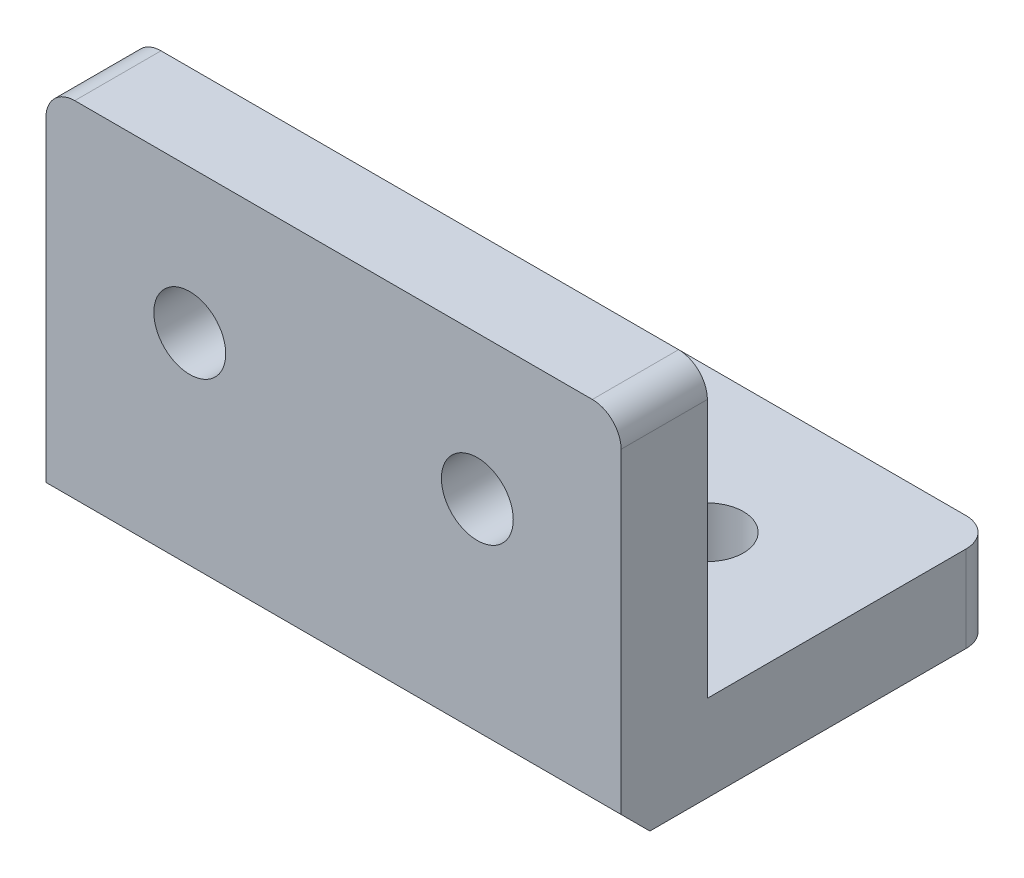
SolidWorks part; units mm, degrees
material "6061 Alloy"
ref_plane "Front Plane" through (0, 0, 0) normal (0, 0, 1) x (1, 0, 0)
ref_plane "Top Plane" through (0, 0, 0) normal (0, 1, 0) x (1, 0, 0)
ref_plane "Right Plane" through (0, 0, 0) normal (1, 0, 0) x (0, 0, -1)
sketch "Sketch1" plane through (0, 0, 0) normal (0, 0, 1) x (1, 0, 0)
  line L0 (-10, 0.75) -> (49990, 0.75) construction
  line L1 (0, 0) -> (0, 36338.3623) construction
  line L3 (-20, -9.25) -> (20, -9.25)
  line L4 (-20, -9.25) -> (-20, 8.75)
  line L5 (-18, 10.75) -> (18, 10.75)
  line L6 (20, -9.25) -> (20, 8.75)
  line L7 (0, 10.75) -> (0, -9.25) construction
  circle A0 centre (-10, 0.75) radius 2.5
  circle A1 centre (10, 0.75) radius 2.5
  arc A2 (18, 10.75) -> (20, 8.75) centre (18, 8.75) cw
  arc A3 (-20, 8.75) -> (-18, 10.75) centre (-18, 8.75) cw
  point P5 (0, 0)
  point P18 (-20, 10.75)
  dimension "D3" = 5
  dimension "D4" = 5
  dimension "D5" = 20
  dimension "D6" = 10
  dimension "D7" = 2
  dimension "D8" = 10
  dimension "D1" = 40
  dimension "D2" = 20
  dimension "D9" = 0.75
extrude "Boss-Extrude2" add sketch "Sketch1" along normal blind 6
sketch "Sketch3" plane through (0, 0, 6) normal (0, 0, 1) x (1, 0, 0)
  line L1 (20, -9.25) -> (-20, -9.25)
  line L2 (20, -9.25) -> (20, -15.25)
  line L3 (20, -15.25) -> (-20, -15.25)
  line L4 (-20, -9.25) -> (-20, -15.25)
  dimension "D1" = 6
extrude "Boss-Extrude3" add sketch "Sketch3" against normal blind 26
sketch "Sketch4" plane through (0, -15.25, 0) normal (0, -1, 0) x (1, 0, 0)
  line L0 (0, 1012) -> (0, 6) construction
  line L1 (-18, -20) -> (18, -20)
  line L2 (-20, -18) -> (-20, 0)
  line L4 (20, -18) -> (20, 0)
  line L5 (0, 0) -> (-20, 0)
  line L6 (-20, 0) -> (20, 0)
  line L7 (0, 0) -> (0, -50000) construction
  line L8 (-20, 6) -> (20, 6) construction
  arc A0 (18, -20) -> (20, -18) centre (18, -18) ccw
  arc A1 (-18, -20) -> (-20, -18) centre (-18, -18) cw
  circle A2 centre (-10, -10) radius 2.5
  circle A3 centre (10, -10) radius 2.5
  point P10 (-20, -20)
  line M4 (-20, 6) -> (-20, -20)
  line M5 (-20, -20) -> (20, -20)
  line M6 (20, -20) -> (20, 6)
  dimension "D1" = 2
  dimension "D2" = 5
  dimension "D3" = 5
  dimension "D4" = 20
  dimension "D5" = 10
  dimension "D6" = 16
  dimension "D7" = 16
extrude "Cut-Extrude2" cut sketch "Sketch4" against normal blind 26 contours A2 | A3 | A1 M5 M4 | A0 M5 M6
chamfer "Chamfer1" distance 2 angle 45 1 edges at (0, -15.25, 6)
